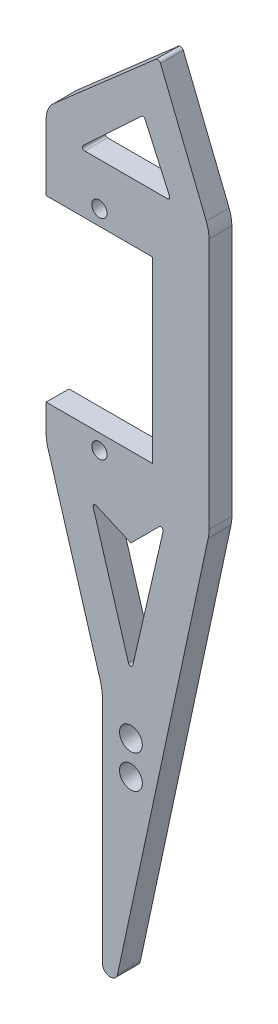
SolidWorks part; units mm, degrees
ref_plane "Front Plane" through (0, 0, 0) normal (0, 0, 1) x (1, 0, 0)
ref_plane "Top Plane" through (0, 0, 0) normal (0, 1, 0) x (1, 0, 0)
ref_plane "Right Plane" through (0, 0, 0) normal (1, 0, 0) x (0, 0, -1)
sketch "Sketch1" plane through (0, 0, 0) normal (0, 0, 1) x (1, 0, 0)
  line L0 (-59.2478, 25.2546) -> (-59.2478, 18.5337)
  line L1 (-59.2478, 18.5337) -> (-45.2478, 18.5337)
  line L2 (-45.2478, 18.5337) -> (-45.2478, -4.9663)
  line L3 (-45.2478, -4.9663) -> (-59.2478, -4.9663)
  line L4 (-59.2478, -4.9663) -> (-59.2478, -8.5755)
  line L5 (-59.0382, -10.008) -> (-52.1733, -32.9639)
  line L6 (-51.8379, -35.256) -> (-51.8379, -65.2023)
  line L7 (-49.8601, -65.4118) -> (-37.9492, -9.825)
  line L8 (-37.8382, -8.7774) -> (-37.8382, 24.2858)
  line L9 (-38.2001, 26.1533) -> (-44.2174, 41.0975)
  line L10 (-44.852, 41.249) -> (-58.2243, 29.5386)
  line L11 (-59.2478, 27.2817) -> (-59.2478, 25.2546)
  line L12 (-46.2434, 33.7262) -> (-43.0285, 26.5763)
  line L13 (-43.3021, 26.1533) -> (-54.1746, 26.1533)
  line L14 (-54.3793, 26.6726) -> (-46.7218, 33.8225)
  line L15 (-48.1073, -15.4361) -> (-44.3788, -11.7076)
  line L16 (-43.8744, -11.9872) -> (-47.853, -29.2279)
  line L17 (-48.4326, -29.2468) -> (-53.0665, -13.8209)
  line L18 (-52.6597, -13.4594) -> (-48.1073, -15.4361)
  arc A0 (-51.8379, -65.2023) -> (-49.8601, -65.4118) centre (-50.8379, -65.2023) ccw
  circle A1 centre (-52.2478, 20.5337) radius 1
  arc A2 (-51.8379, -35.256) -> (-52.1733, -32.9639) centre (-59.8379, -35.256) ccw
  arc A3 (-58.2243, 29.5386) -> (-59.2478, 27.2817) centre (-56.2478, 27.2817) ccw
  arc A4 (-44.2174, 41.0975) -> (-44.852, 41.249) centre (-44.5885, 40.9481) ccw
  arc A5 (-59.0382, -10.008) -> (-59.2478, -8.5755) centre (-54.2478, -8.5755) cw
  arc A6 (-37.9492, -9.825) -> (-37.8382, -8.7774) centre (-42.8382, -8.7774) ccw
  arc A7 (-37.8382, 24.2858) -> (-38.2001, 26.1533) centre (-42.8382, 24.2858) ccw
  circle A8 centre (-52.2478, -6.9663) radius 1
  circle A9 centre (-48.1073, -37.6825) radius 1.5
  circle A10 centre (-48.1073, -42.0509) radius 1.5
  arc A11 (-46.7218, 33.8225) -> (-46.2434, 33.7262) centre (-46.517, 33.6032) cw
  arc A12 (-43.3021, 26.1533) -> (-43.0285, 26.5763) centre (-43.3021, 26.4533) ccw
  arc A13 (-54.3793, 26.6726) -> (-54.1746, 26.1533) centre (-54.1746, 26.4533) ccw
  arc A14 (-48.4326, -29.2468) -> (-47.853, -29.2279) centre (-48.1453, -29.1605) ccw
  arc A15 (-53.0665, -13.8209) -> (-52.6597, -13.4594) centre (-52.7792, -13.7345) cw
  arc A16 (-43.8744, -11.9872) -> (-44.3788, -11.7076) centre (-44.1667, -11.9197) ccw
  dimension "D2" = 0.4
  dimension "D3" = 8
  dimension "D4" = 2
  dimension "D5" = 2
  dimension "D7" = 2
  dimension "D8" = 3
  dimension "D9" = 3
  dimension "D10" = 27.5
  dimension "D11" = 0.3
  dimension "D12" = 0.3
  dimension "D13" = 1
  dimension "D6" = 2
extrude "Boss-Extrude1" add sketch "Sketch1" along normal blind 3
